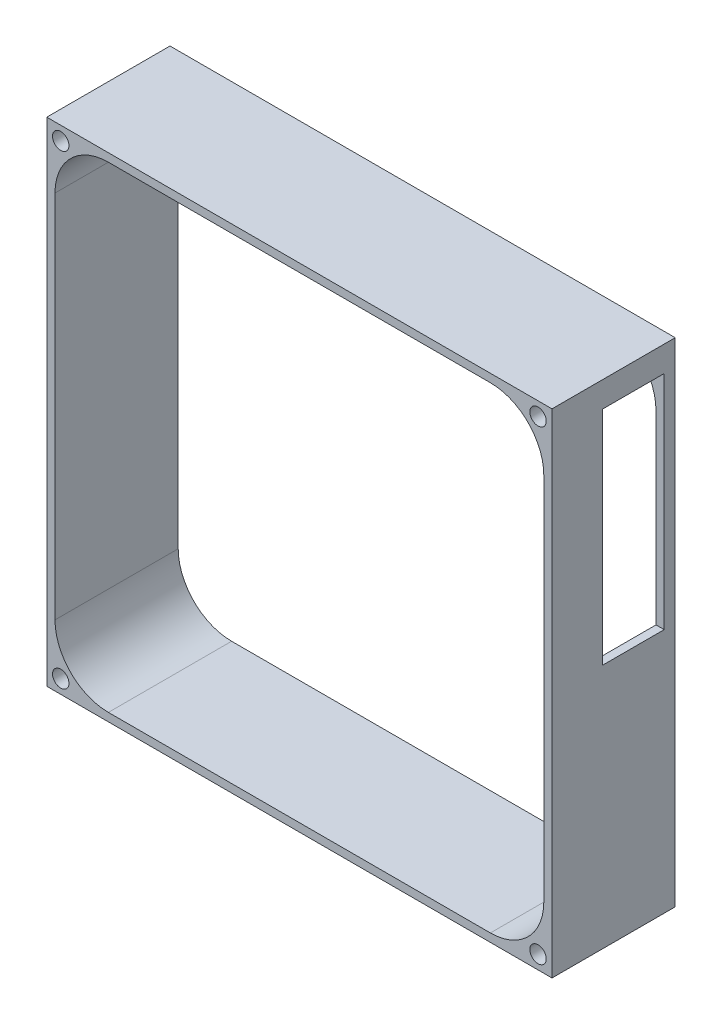
SolidWorks part; units mm, degrees
ref_plane "前视基准面" through (0, 0, 0) normal (0, 0, 1) x (1, 0, 0)
ref_plane "上视基准面" through (0, 0, 0) normal (0, 1, 0) x (1, 0, 0)
ref_plane "右视基准面" through (0, 0, 0) normal (1, 0, 0) x (0, 0, -1)
sketch "草图1" plane through (0, 0, 0) normal (0, 0, 1) x (1, 0, 0)
  line L0 (-25.9069, 113.2078) -> (-25.9069, -6.7922) construction
  line L1 (-89.6685, 105.2144) -> (30.3315, 105.2144) construction
  line L2 (-89.6685, 105.2144) -> (-89.6685, 51.2144) construction
  line L3 (-89.6685, 51.2144) -> (30.3315, 51.2144) construction
  line L4 (30.3315, 105.2144) -> (30.3315, 51.2144) construction
  line L5 (-84.492, 46.474) -> (-40.492, 46.474) construction
  line L6 (-84.492, 46.474) -> (-84.492, 2.474) construction
  line L7 (-84.492, 2.474) -> (-40.492, 2.474) construction
  line L8 (-40.492, 46.474) -> (-40.492, 2.474) construction
  line L9 (93.3407, 114.5084) -> (131.3407, 114.5084) construction
  line L10 (93.3407, 114.5084) -> (93.3407, 91.5084) construction
  line L11 (93.3407, 91.5084) -> (131.3407, 91.5084) construction
  line L12 (131.3407, 114.5084) -> (131.3407, 91.5084) construction
  line L13 (93.6009, 60.7312) -> (136.6009, 60.7312) construction
  line L14 (93.6009, 60.7312) -> (93.6009, 36.7312) construction
  line L15 (93.6009, 36.7312) -> (136.6009, 36.7312) construction
  line L16 (136.6009, 60.7312) -> (136.6009, 36.7312) construction
  line L17 (-87.4069, 113.2078) -> (35.5931, 113.2078)
  line L18 (-87.4069, 113.2078) -> (-87.4069, -6.7922)
  line L19 (-87.4069, -6.7922) -> (35.5931, -6.7922)
  line L20 (35.5931, 113.2078) -> (35.5931, -6.7922)
  line L21 (-87.4069, 53.2078) -> (35.5931, 53.2078) construction
  line L22 (-72.4069, 111.2078) -> (20.5931, 111.2078)
  line L23 (33.5931, 98.2078) -> (33.5931, 8.2078)
  line L24 (-72.4069, -4.7922) -> (20.5931, -4.7922)
  line L25 (-85.4069, 98.2078) -> (-85.4069, 8.2078)
  line L26 (-85.4069, 111.2078) -> (-85.4069, -4.7922) construction
  line L27 (-85.4069, -4.7922) -> (33.5931, -4.7922) construction
  line L28 (33.5931, 111.2078) -> (33.5931, -4.7922) construction
  line L29 (-85.4069, 111.2078) -> (33.5931, 111.2078) construction
  circle A0 centre (-84.0084, 109.8944) radius 2
  circle A1 centre (32.1945, 109.8944) radius 2
  circle A2 centre (32.1945, -3.4788) radius 2
  circle A3 centre (-84.0084, -3.4788) radius 2
  arc A4 (-85.4069, 8.2078) -> (-72.4069, -4.7922) centre (-72.4069, 8.2078) ccw
  arc A5 (20.5931, -4.7922) -> (33.5931, 8.2078) centre (20.5931, 8.2078) ccw
  arc A6 (33.5931, 98.2078) -> (20.5931, 111.2078) centre (20.5931, 98.2078) ccw
  arc A7 (-72.4069, 111.2078) -> (-85.4069, 98.2078) centre (-72.4069, 98.2078) ccw
  point P48 (-83.8069, 110.2078)
  point P49 (-84.0084, 109.8944)
  dimension "D11" = 4
  dimension "D13" = 13
  dimension "D1" = 120
  dimension "D2" = 54
  dimension "D3" = 44
  dimension "D4" = 44
  dimension "D5" = 38
  dimension "D6" = 23
  dimension "D7" = 43
  dimension "D8" = 24
  dimension "D9" = 123
  dimension "D10" = 120
  dimension "D12" = 2
extrude "凸台-拉伸1" add sketch "草图1" along normal blind 30
sketch "草图2" plane through (35.5931, 0, 0) normal (1, 0, 0) x (0, 0, -1)
  line L1 (-17.6863, 106.9993) -> (-2.6863, 106.9993)
  line L2 (-17.6863, 106.9993) -> (-17.6863, 52.9993)
  line L3 (-17.6863, 52.9993) -> (-2.6863, 52.9993)
  line L4 (-2.6863, 106.9993) -> (-2.6863, 52.9993)
  dimension "D1" = 54
  dimension "D2" = 15
extrude "切除-拉伸1" cut sketch "草图2" against normal blind 120
